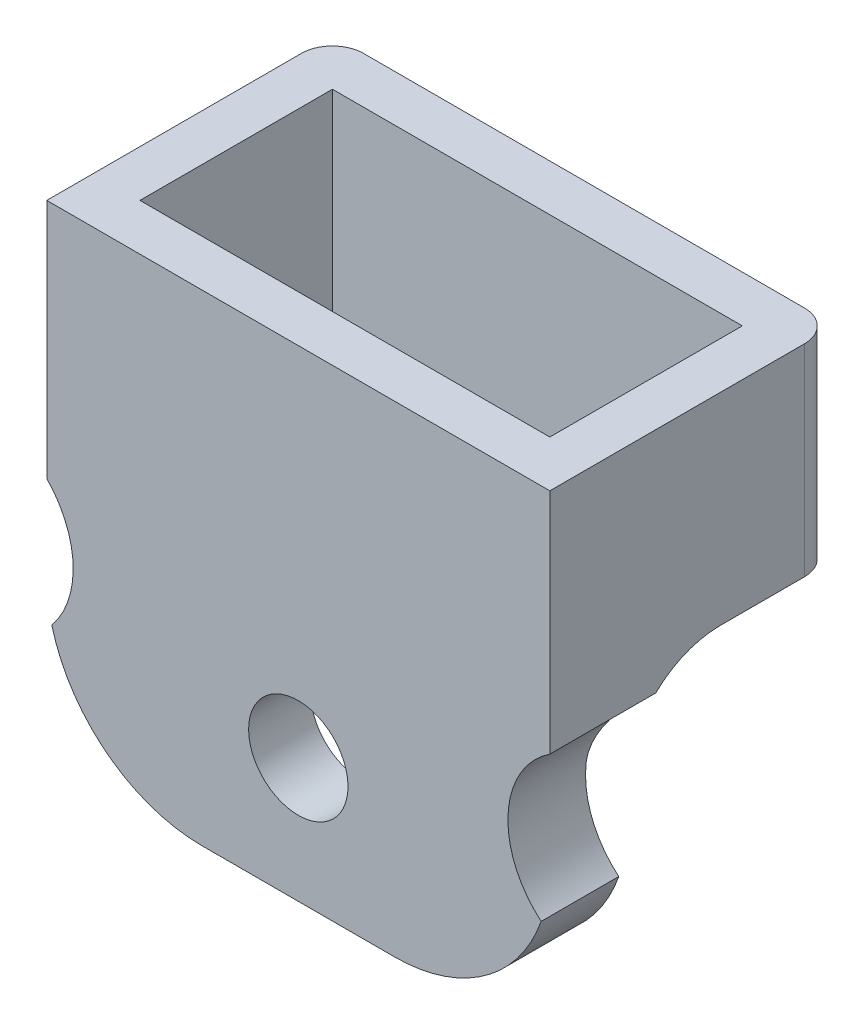
SolidWorks part; units mm, degrees
ref_plane "Alzado" through (0, 0, 0) normal (0, 0, 1) x (1, 0, 0)
ref_plane "Planta" through (0, 0, 0) normal (0, 1, 0) x (1, 0, 0)
ref_plane "Vista lateral" through (0, 0, 0) normal (1, 0, 0) x (0, 0, -1)
sketch "Croquis1" plane through (0, 0, 0) normal (0, 1, 0) x (1, 0, 0)
  line L0 (-1.5, 7.7) -> (14.7, 7.7)
  line L1 (0, 0) -> (13.2, 0)
  line L2 (0, 0) -> (0, 6.2)
  line L3 (0, 6.2) -> (13.2, 6.2)
  line L4 (13.2, 0) -> (13.2, 6.2)
  line L5 (14.7, -1.5) -> (14.7, 7.7)
  line L6 (-1.5, -1.5) -> (14.7, -1.5)
  line L7 (-1.5, -1.5) -> (-1.5, 7.7)
  dimension "D1" = 13.2
  dimension "D2" = 6.2
  dimension "D3" = 1.5
extrude "Saliente-Extruir1" add sketch "Croquis1" along normal blind 6.5
sketch "Croquis3" plane through (0, 0, 0) normal (0, -1, 0) x (1, 0, 0)
  line L0 (-1.5, -7.7) -> (-1.5, 1.5) construction
  line L1 (14.7, 1.5) -> (-1.5, 1.5)
  line L2 (14.7, 1.5) -> (14.7, -1)
  line L3 (14.7, -1) -> (-1.5, -1)
  line L4 (-1.5, 1.5) -> (-1.5, -1)
  dimension "D1" = 2.5
extrude "Saliente-Extruir2" add sketch "Croquis3" along normal blind 9
sketch "Croquis4" plane through (0, 0, -1) normal (0, 0, -1) x (-1, 0, 0)
  line L0 (-14.7, -9) -> (-14.7, 0) construction
  line L3 (1.5, -9) -> (-14.7, -9) construction
  circle A0 centre (-6.6, -5) radius 1.6
  dimension "D1" = 3.2
  dimension "D2" = 8.1
  dimension "D3" = 4
extrude "Cortar-Extruir1" cut sketch "Croquis4" against normal up to surface (2.5 mm away) up to face at (6.6, -1.25, 1.5)
fillet "Redondeo1" radius 1 2 edges at (14.7, 3.25, -7.7) (-1.5, 3.25, -7.7)
fillet "Redondeo2" radius 5 2 edges at (14.7, -9, 0.25) (-1.5, -9, 0.25)
fillet "Redondeo3" radius 3 2 edges at (13.95, 0, -1) (-0.75, 0, -1)
sketch "Croquis5" plane through (0, 0, -7.7) normal (0, 0, -1) x (-1, 0, 0)
  line L0 (-13.7, 6.5) -> (0.5, 6.5) construction
  circle A0 centre (-16.35, -3.35) radius 3
  circle A1 centre (3.65, -3.35) radius 3
  circle A2 centre (-6.6, -5) radius 1.6 construction
  dimension "D1" = 6
  dimension "D3" = 9.85
  dimension "D2" = 9.85
  dimension "D4" = 9.75
  dimension "D5" = 10.25
extrude "Cortar-Extruir2" cut sketch "Croquis5" against normal up to surface (9.2 mm away) up to face at (5, -5, 1.5)
sketch "Croquis6" plane through (0, 0, -1) normal (0, 0, -1) x (-1, 0, 0)
  circle A0 centre (-6.6, -5) radius 2.9
  dimension "D1" = 5.8
extrude "Cortar-Extruir3" cut sketch "Croquis6" against normal blind 0.5
